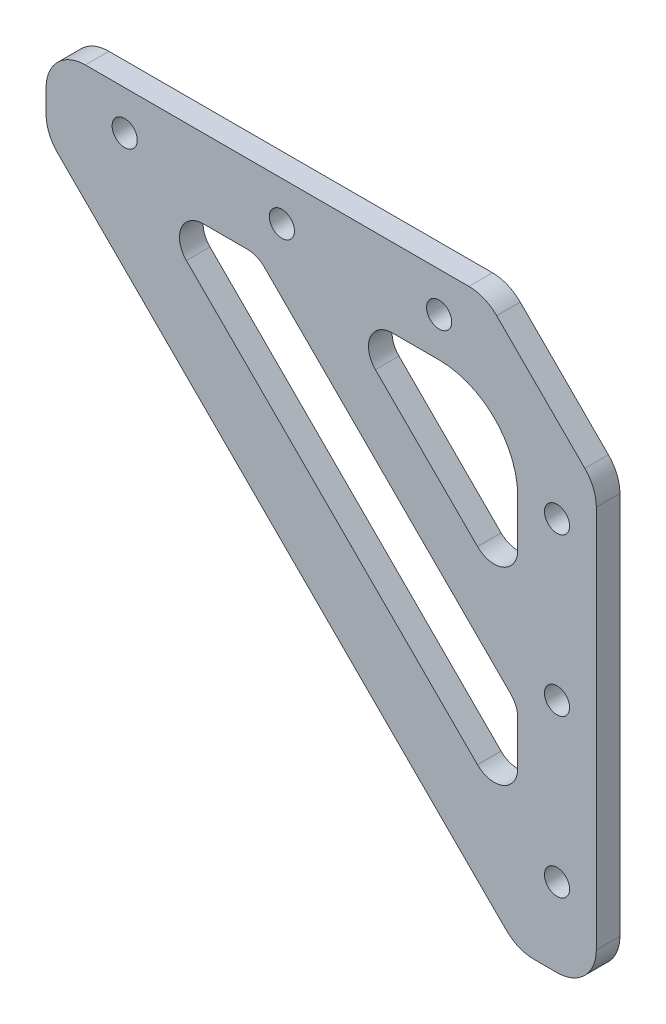
SolidWorks part; units mm, degrees
ref_plane "前视基准面" through (0, 0, 0) normal (0, 0, 1) x (1, 0, 0)
ref_plane "上视基准面" through (0, 0, 0) normal (0, 1, 0) x (1, 0, 0)
ref_plane "右视基准面" through (0, 0, 0) normal (1, 0, 0) x (0, 0, -1)
sketch "草图1" plane through (0, 0, 0) normal (0, 0, 1) x (1, 0, 0)
  line L0 (0, 0) -> (-70, 0)
  line L1 (-70, 0) -> (-70, -10)
  line L2 (-70, -10) -> (-10, -10)
  line L6 (-70, -5) -> (49930, -5) construction
  line L7 (2.5, 2.5) -> (-35352.8391, -35352.8391) construction
  line L8 (-10, -70) -> (-10, -10)
  line L9 (0, -70) -> (-10, -70)
  line L10 (0, 0) -> (0, -70)
  circle A1 centre (-20, -5) radius 1.6
  circle A2 centre (-5, -20) radius 1.6
  circle A4 centre (-40, -5) radius 1.6
  circle A5 centre (-60, -5) radius 1.6
  circle A6 centre (-5, -60) radius 1.6
  circle A7 centre (-5, -40) radius 1.6
  point P9 (-70, -5)
  dimension "D3" = 3
  dimension "D4" = 3.2
  dimension "D5" = 15
  dimension "D1" = 10
  dimension "D2" = 45
  dimension "D6" = 20
  dimension "D7" = 70
extrude "凸台-拉伸1" add sketch "草图1" along normal blind 3
sketch "草图2" plane through (0, 0, 3) normal (0, 0, 1) x (1, 0, 0)
  line L0 (-70, -10) -> (-10, -70)
  line L1 (-10, -70) -> (-10, -57.2721)
  line L2 (-10, -10) -> (-10, -70) construction
  line L3 (-10, -57.2721) -> (-57.2721, -10)
  line L4 (-70, -10) -> (-10, -10) construction
  line L5 (-57.2721, -10) -> (-70, -10)
  dimension "D1" = 9
extrude "凸台-拉伸2" add sketch "草图2" against normal blind 3
sketch "草图3" plane through (0, 0, 3) normal (0, 0, 1) x (1, 0, 0)
  line L0 (-14.1421, 0) -> (0, -14.1421)
  line L1 (0, 0) -> (-70, 0) construction
  line L2 (0, -70) -> (0, 0) construction
  line L3 (-10, -57.2721) -> (-57.2721, -10) construction
  dimension "D1" = 10
extrude "切除-拉伸1" cut sketch "草图3" against normal blind 3 and the other way through all
fillet "圆角1" radius 5 6 edges at (-10, -70, 1.5) (0, -70, 1.5) (-70, -10, 1.5) (-70, 0, 1.5) (0, -14.1421, 1.5) (-14.1421, 0, 1.5)
sketch "草图4" plane through (0, 0, 3) normal (0, 0, 1) x (1, 0, 0)
  line L0 (-43.1299, -10) -> (-10, -43.1299)
  line L1 (-57.2721, -10) -> (-10, -10) construction
  line L2 (-10, -10) -> (-10, -57.2721) construction
  line L3 (-10, -43.1299) -> (-10, -33.2304)
  line L4 (-10, -33.2304) -> (-33.2304, -10)
  line L5 (-33.2304, -10) -> (-43.1299, -10)
  line L6 (-68.5355, -11.4645) -> (-11.4645, -68.5355) construction
  line L7 (-10, -57.2721) -> (-57.2721, -10) construction
  dimension "D1" = 7
  dimension "D2" = 10
extrude "凸台-拉伸3" add sketch "草图4" against normal through all
fillet "圆角2" radius 3 6 edges at (-10, -57.2721, 1.5) (-57.2721, -10, 1.5) (-10, -43.1299, 1.5) (-43.1299, -10, 1.5) (-10, -33.2304, 1.5) (-33.2304, -10, 1.5)
fillet "圆角3" radius 10 1 edges at (-10, -10, 1.5)
